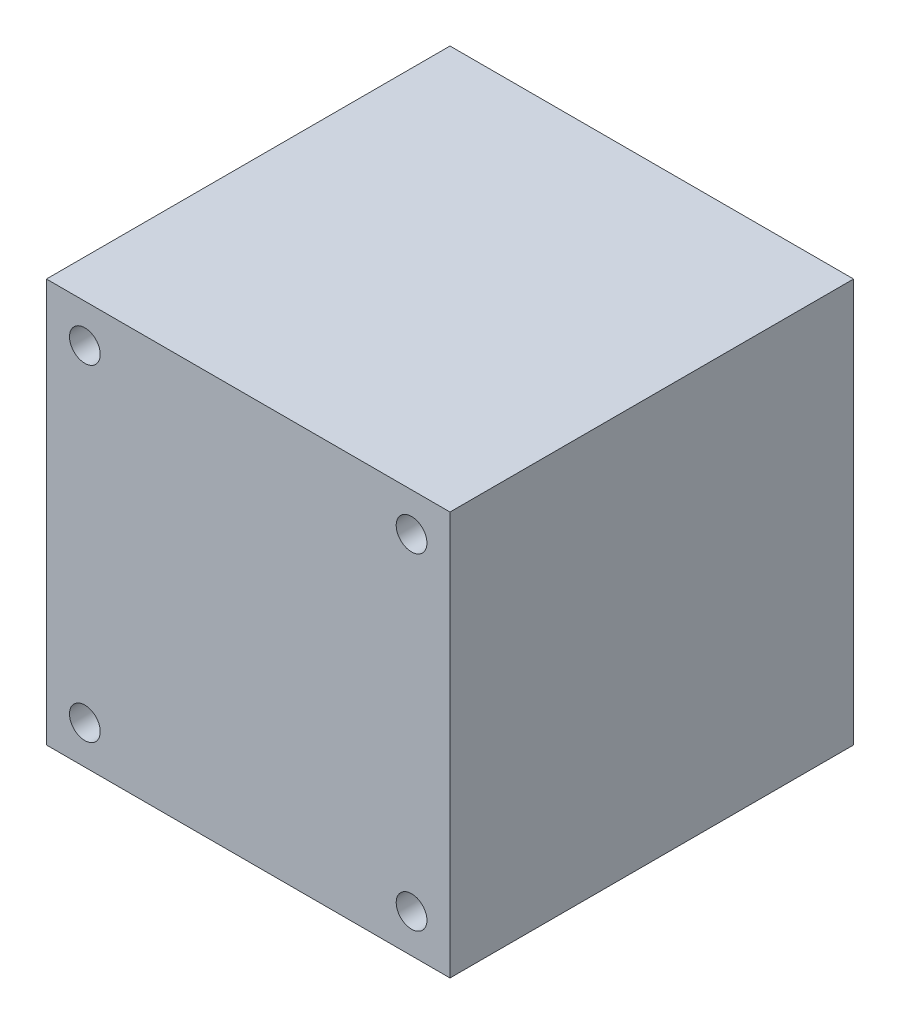
SolidWorks part; units mm, degrees
ref_plane "Front Plane" through (0, 0, 0) normal (0, 0, 1) x (1, 0, 0)
ref_plane "Top Plane" through (0, 0, 0) normal (0, 1, 0) x (1, 0, 0)
ref_plane "Right Plane" through (0, 0, 0) normal (1, 0, 0) x (0, 0, -1)
sketch "Sketch1" plane through (0, 0, 0) normal (0, 0, 1) x (1, 0, 0)
  line L0 (-17, 17) -> (-17, -17) construction
  line L1 (-21, -21) -> (21, -21)
  line L2 (-21, -21) -> (-21, 21)
  line L3 (-21, 21) -> (21, 21)
  line L4 (21, -21) -> (21, 21)
  line L5 (-21, -21) -> (21, 21) construction
  line L6 (-21, 21) -> (21, -21) construction
  line L7 (-17, 17) -> (17, 17) construction
  line L8 (-17, -17) -> (17, -17) construction
  line L9 (17, -17) -> (17, 17) construction
  circle A0 centre (-17, 17) radius 1.6
  circle A1 centre (-17, -17) radius 1.6
  circle A2 centre (17, -17) radius 1.6
  circle A3 centre (17, 17) radius 1.6
  point P0 (0, 0)
  dimension "D4" = 34
  dimension "D2" = 3.2
  dimension "D5" = 3.2
  dimension "D6" = 3.2
  dimension "D7" = 3.2
  dimension "D1" = 42
  dimension "D3" = 34
extrude "Boss-Extrude1" add sketch "Sketch1" along normal blind 42
